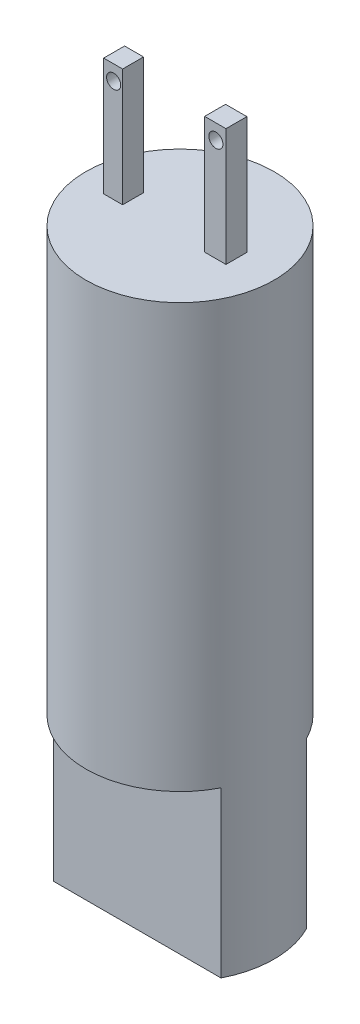
SolidWorks part; units mm, degrees
material "Galvanized Steel"
ref_plane "Front Plane" through (0, 0, 0) normal (0, 0, 1) x (1, 0, 0)
ref_plane "Top Plane" through (0, 0, 0) normal (0, 1, 0) x (1, 0, 0)
ref_plane "Right Plane" through (0, 0, 0) normal (1, 0, 0) x (0, 0, -1)
sketch "Sketch2" plane through (0, 0, 0) normal (0, 1, 0) x (1, 0, 0)
  circle A0 centre (0, 0) radius 4
extrude "Boss-Extrude1" add sketch "Sketch2" along normal blind 25
sketch "Sketch3" plane through (0, 0, 0) normal (0, -1, 0) x (1, 0, 0)
  line L1 (-4.4264, 1.8192) -> (4.4264, 1.8192)
  line L3 (-4.4264, -1.8192) -> (4.4264, -1.8192)
  arc A0 (-4.4264, 1.8192) -> (4.4264, 1.8192) centre (0, -1.0677) cw
  arc A1 (-4.4264, -1.8192) -> (4.4264, -1.8192) centre (0, 0.8403) ccw
  point P0 (0, 0)
extrude "Cut-Extrude1" cut sketch "Sketch3" against normal blind 7
sketch "Sketch4" plane through (0, 7, 0) normal (0, -1, 0) x (1, 0, 0)
  circle A0 centre (0, 0) radius 4
sketch "Sketch6" plane through (0, 25, 0) normal (0, 1, 0) x (1, 0, 0)
  line L1 (-2.8001, 0.4443) -> (-1.9953, 0.4443)
  line L2 (-2.8001, 0.4443) -> (-2.8001, -0.4443)
  line L3 (-2.8001, -0.4443) -> (-1.9953, -0.4443)
  line L4 (-1.9953, 0.4443) -> (-1.9953, -0.4443)
  line L5 (-2.8001, 0.4443) -> (-1.9953, -0.4443) construction
  line L6 (-2.8001, -0.4443) -> (-1.9953, 0.4443) construction
  line L7 (1.4922, 0.4443) -> (2.3977, 0.4443)
  line L8 (1.4922, 0.4443) -> (1.4922, -0.4443)
  line L9 (1.4922, -0.4443) -> (2.3977, -0.4443)
  line L10 (2.3977, 0.4443) -> (2.3977, -0.4443)
  line L11 (1.4922, 0.4443) -> (2.3977, -0.4443) construction
  line L12 (1.4922, -0.4443) -> (2.3977, 0.4443) construction
  point P0 (-2.3977, 0)
  point P5 (1.945, 0)
extrude "Boss-Extrude2" add sketch "Sketch6" along normal blind 5
sketch "Sketch7" plane through (0, 0, -0.4443) normal (0, 0, -1) x (-1, 0, 0)
  circle A0 centre (-1.9682, 29.3604) radius 0.3
  circle A1 centre (2.3776, 29.3604) radius 0.3
extrude "Cut-Extrude2" cut sketch "Sketch7" against normal blind 5
